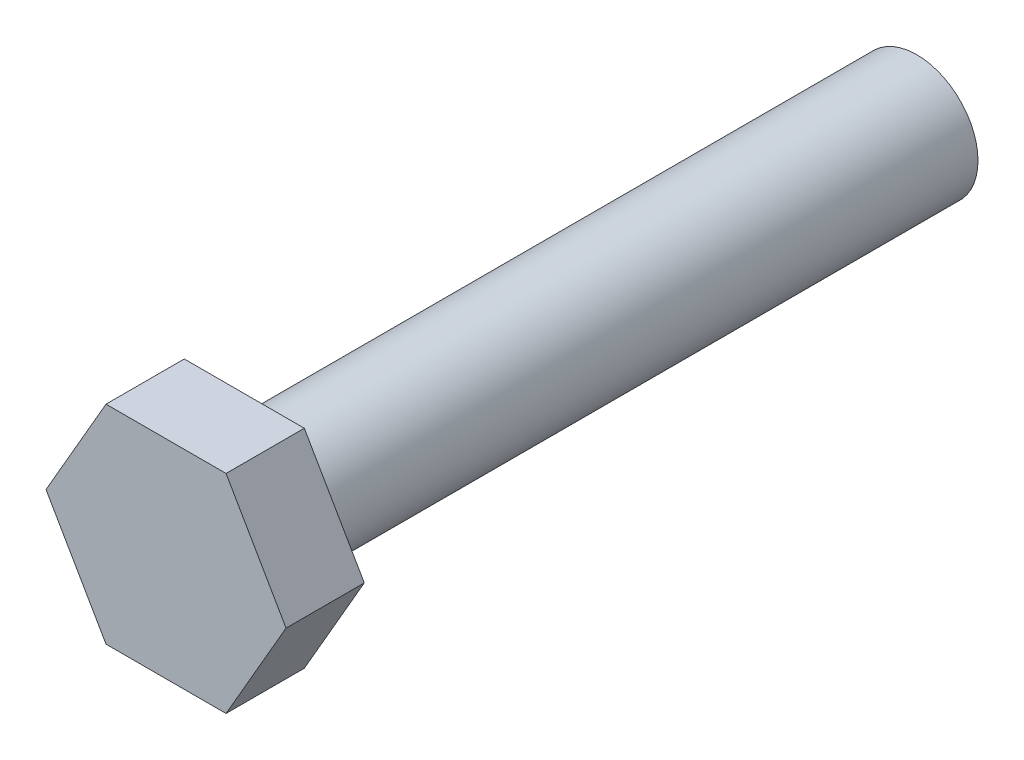
SolidWorks part; units mm, degrees
material "AISI 304"
ref_plane "Front Plane" through (0, 0, 0) normal (0, 0, 1) x (1, 0, 0)
ref_plane "Top Plane" through (0, 0, 0) normal (0, 1, 0) x (1, 0, 0)
ref_plane "Right Plane" through (0, 0, 0) normal (1, 0, 0) x (0, 0, -1)
sketch "Sketch1" plane through (0, 0, 0) normal (0, 0, 1) x (1, 0, 0)
  circle A0 centre (0, 0) radius 5
  dimension "D1" = 10
extrude "Extrude1" add sketch "Sketch1" against normal blind 55
cosmetic thread "Cosmetic Thread1" parameters "D1"=55, "D2"=6.5278
sketch "Sketch2" plane through (0, 0, 0) normal (0, 0, 1) x (1, 0, 0)
  line L1 (-4.9075, 8.5) -> (-9.815, 0)
  line L2 (-9.815, 0) -> (-4.9075, -8.5)
  line L3 (-4.9075, -8.5) -> (4.9075, -8.5)
  line L4 (4.9075, -8.5) -> (9.815, 0)
  line L5 (9.815, 0) -> (4.9075, 8.5)
  line L6 (4.9075, 8.5) -> (-4.9075, 8.5)
  circle A0 centre (0, 0) radius 8.5 construction
  dimension "D1" = 17
extrude "Extrude2" add sketch "Sketch2" along normal blind 6.4
